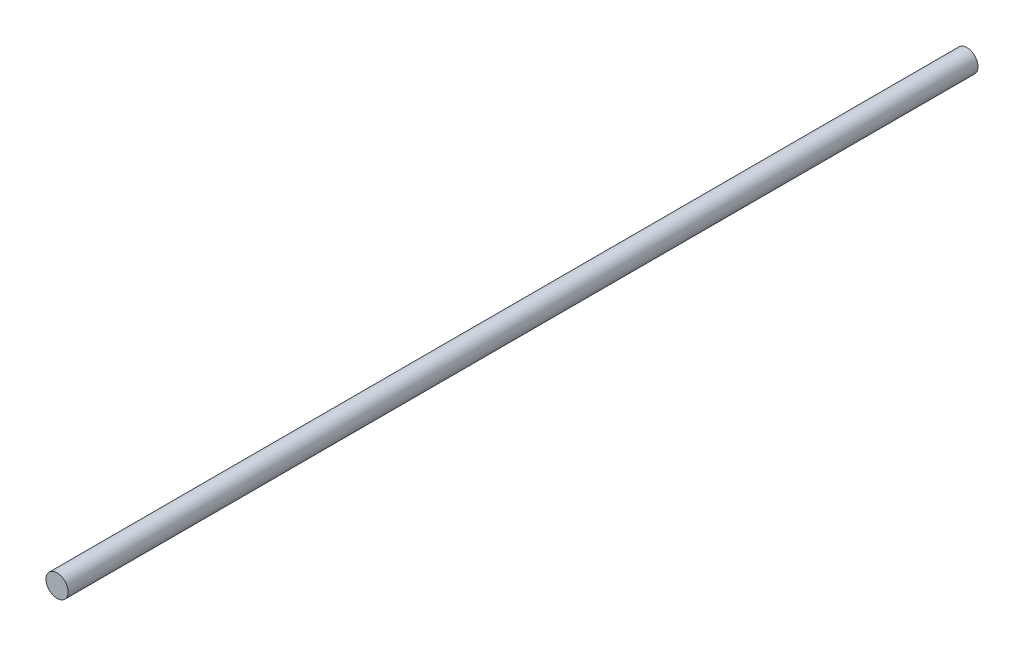
SolidWorks part; units mm, degrees
ref_plane "Front Plane" through (0, 0, 0) normal (0, 0, 1) x (1, 0, 0)
ref_plane "Top Plane" through (0, 0, 0) normal (0, 1, 0) x (1, 0, 0)
ref_plane "Right Plane" through (0, 0, 0) normal (1, 0, 0) x (0, 0, -1)
sketch "Sketch1" plane through (0, 0, 0) normal (0, 0, 1) x (1, 0, 0)
  circle A0 centre (0, 0) radius 2
  dimension "D1" = 4
extrude "Boss-Extrude1" add sketch "Sketch1" along normal mid plane 164
